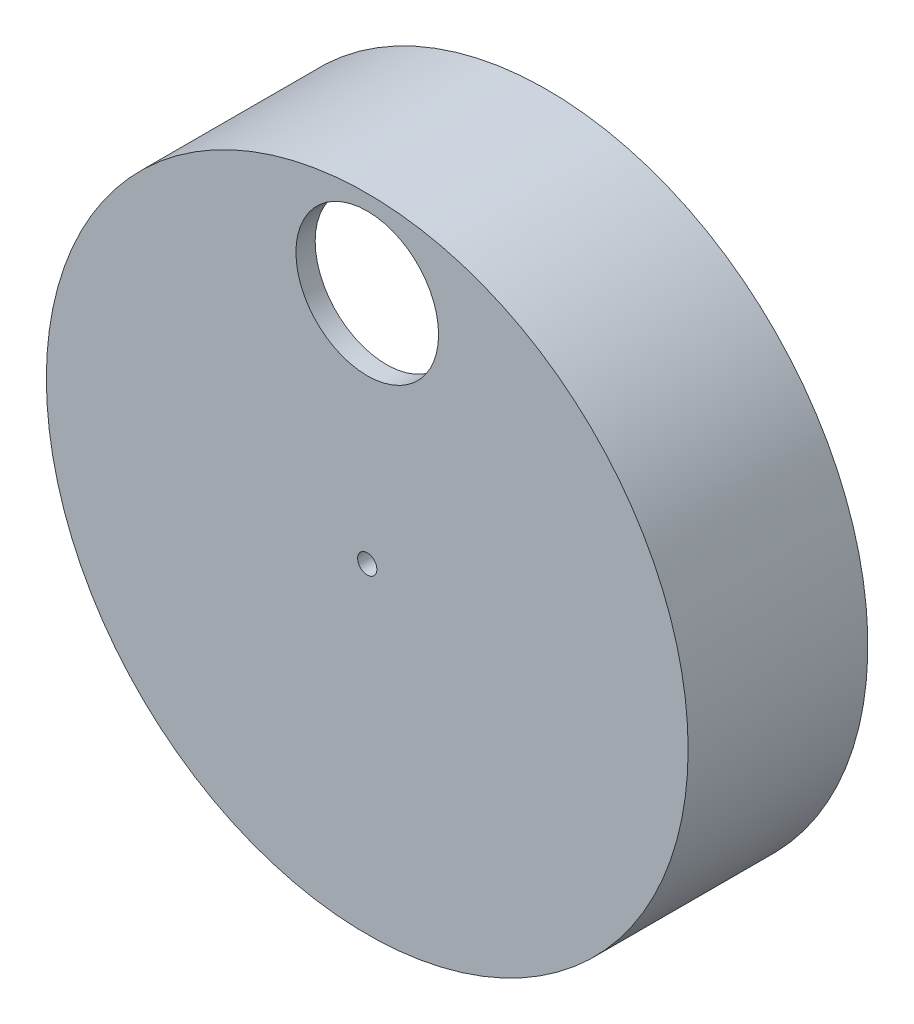
SolidWorks part; units mm, degrees
ref_plane "Front Plane" through (0, 0, 0) normal (0, 0, 1) x (1, 0, 0)
ref_plane "Top Plane" through (0, 0, 0) normal (0, 1, 0) x (1, 0, 0)
ref_plane "Right Plane" through (0, 0, 0) normal (1, 0, 0) x (0, 0, -1)
sketch "Sketch1" plane through (0, 0, 0) normal (0, 0, 1) x (1, 0, 0)
  circle A0 centre (0, 0) radius 100
extrude "Boss-Extrude1" add sketch "Sketch1" along normal blind 6 contours A0
sketch "Sketch2" plane through (0, 0, 0) normal (0, 0, -1) x (-1, 0, 0)
  circle A0 centre (0, 0) radius 100
  circle A1 centre (0, 0) radius 97
  dimension "D1" = 194
extrude "Boss-Extrude2" add sketch "Sketch2" along normal blind 50
sketch "Sketch4" plane through (0, 0, 0) normal (0, 0, -1) x (-1, 0, 0)
  line L0 (0, 0) -> (0, 100) construction
  circle A0 centre (0, 0) radius 100 construction
  circle A1 centre (0, 73) radius 22.225
  circle A2 centre (0, 0) radius 97 construction
  dimension "D1" = 44.45
  dimension "D2" = 73
extrude "Cut-Extrude2" cut sketch "Sketch4" against normal blind 50
sketch "Sketch5" plane through (0, 0, 0) normal (0, 0, -1) x (-1, 0, 0)
  circle A0 centre (0, 0) radius 3
  dimension "D1" = 6
extrude "Cut-Extrude3" cut sketch "Sketch5" against normal blind 50
